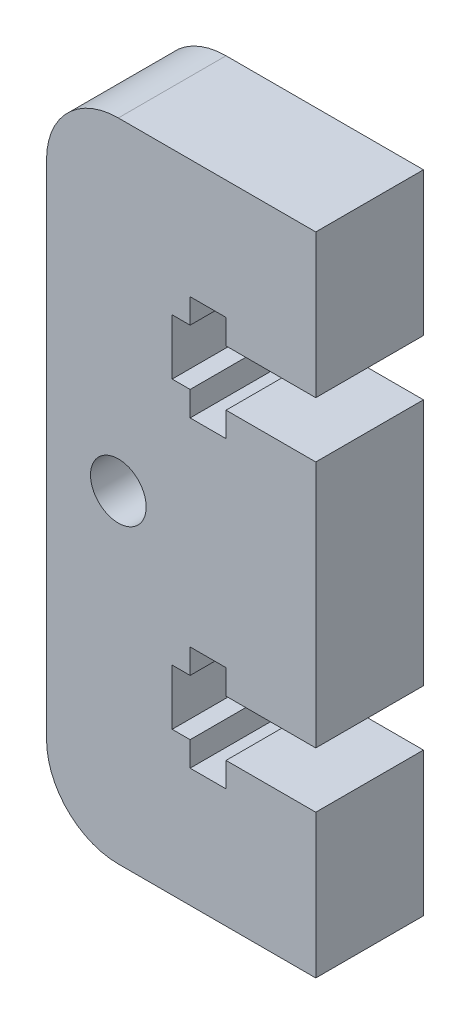
SolidWorks part; units mm, degrees
ref_plane "Płaszczyzna przednia" through (0, 0, 0) normal (0, 0, 1) x (1, 0, 0)
ref_plane "Płaszczyzna górna" through (0, 0, 0) normal (0, 1, 0) x (1, 0, 0)
ref_plane "Płaszczyzna prawa" through (0, 0, 0) normal (1, 0, 0) x (0, 0, -1)
sketch "Szkic1" plane through (302.1513, 0, 0) normal (0, 0, -1) x (-1, 0, 0)
  line L0 (-882.3906, 236.7278) -> (-882.3906, 200.7278)
  line L1 (-882.3906, 236.7278) -> (-871.3906, 236.7278)
  line L2 (-882.3906, 200.7278) -> (-871.3906, 200.7278)
  line L3 (-867.3906, 232.7278) -> (-867.3906, 204.7278)
  arc A0 (-871.3906, 200.7278) -> (-867.3906, 204.7278) centre (-871.3906, 204.7278) ccw
  arc A1 (-871.3906, 236.7278) -> (-867.3906, 232.7278) centre (-871.3906, 232.7278) cw
  dimension "D3" = 4
  dimension "D1" = 15
  dimension "D2" = 36
extrude "Dodanie-wyciągnięcie1" add sketch "Szkic1" along normal blind 6
sketch "Szkic2" plane through (1169.5419, 0, -6) normal (0, 0, 1) x (1, 0, 0)
  line L0 (15, 228.7278) -> (15, 225.6278)
  line L1 (15, 228.7278) -> (10, 228.7278)
  line L2 (15, 225.6278) -> (10, 225.6278)
  line L3 (7, 228.7278) -> (7, 225.6278)
  line L4 (15, 236.7278) -> (15, 200.7278) construction
  line L5 (8, 230.1028) -> (8, 228.7278)
  line L6 (8, 230.1028) -> (10, 230.1028)
  line L7 (8, 224.2528) -> (10, 224.2528)
  line L8 (10, 230.1028) -> (10, 228.7278)
  line L9 (8, 228.7278) -> (7, 228.7278)
  line L10 (8, 225.6278) -> (8, 224.2528)
  line L11 (8, 225.6278) -> (7, 225.6278)
  line L12 (10, 225.6278) -> (10, 224.2528)
  line L13 (4, 236.7278) -> (15, 236.7278) construction
  dimension "D1" = 3.1
  dimension "D2" = 5.85
  dimension "D3" = 1.375
  dimension "D4" = 1
  dimension "D5" = 8
  dimension "D6" = 2
  dimension "D7" = 8
extrude "Wytnij-wyciągnięcie1" cut sketch "Szkic2" along normal blind 15
pattern_linear "Szyk liniowy1" count 2 spacing 16.9 along (0, -1, 0) of "Wytnij-wyciągnięcie1"
sketch "Szkic3" plane through (0, 0, -6) normal (0, 0, -1) x (-1, 0, 0)
  line L0 (-1173.5419, 236.7278) -> (-1184.5419, 236.7278) construction
  line L1 (-1169.5419, 204.7278) -> (-1169.5419, 232.7278) construction
  circle A0 centre (-1173.5419, 218.7278) radius 1.55
  dimension "D1" = 3.1
  dimension "D2" = 18
  dimension "D3" = 4
extrude "Wytnij-wyciągnięcie2" cut sketch "Szkic3" against normal blind 15
equation "\"tolerancja_wpusy\"=0.2"
equation "\"dlugosc_wpustu_duzy\"=20"
equation "\"srednica_otworu_M3\"=3.1"
equation "\"szerokosc_nogi_T\"=3.1"
equation "\"dlugosc_T_30\"=11"
equation "\"grubosc_na_nakretke_kwadrat\"=2"
equation "\"szerokosc_na_nakretke_kwadrat\"=5.85"
equation "\"wyokosc_nadstawki_T\"=0.5"
equation "\"dlugosc_T_20_6\"=14"
equation "\"D1@Szkic2\"=\"szerokosc_nogi_T\""
equation "\"D2@Szkic2\"=\"szerokosc_na_nakretke_kwadrat\""
equation "\"D3@Szkic2\"=(\"szerokosc_na_nakretke_kwadrat\"-\"szerokosc_nogi_T\")/2"
equation "\"D6@Szkic2\"=\"grubosc_na_nakretke_kwadrat\""
